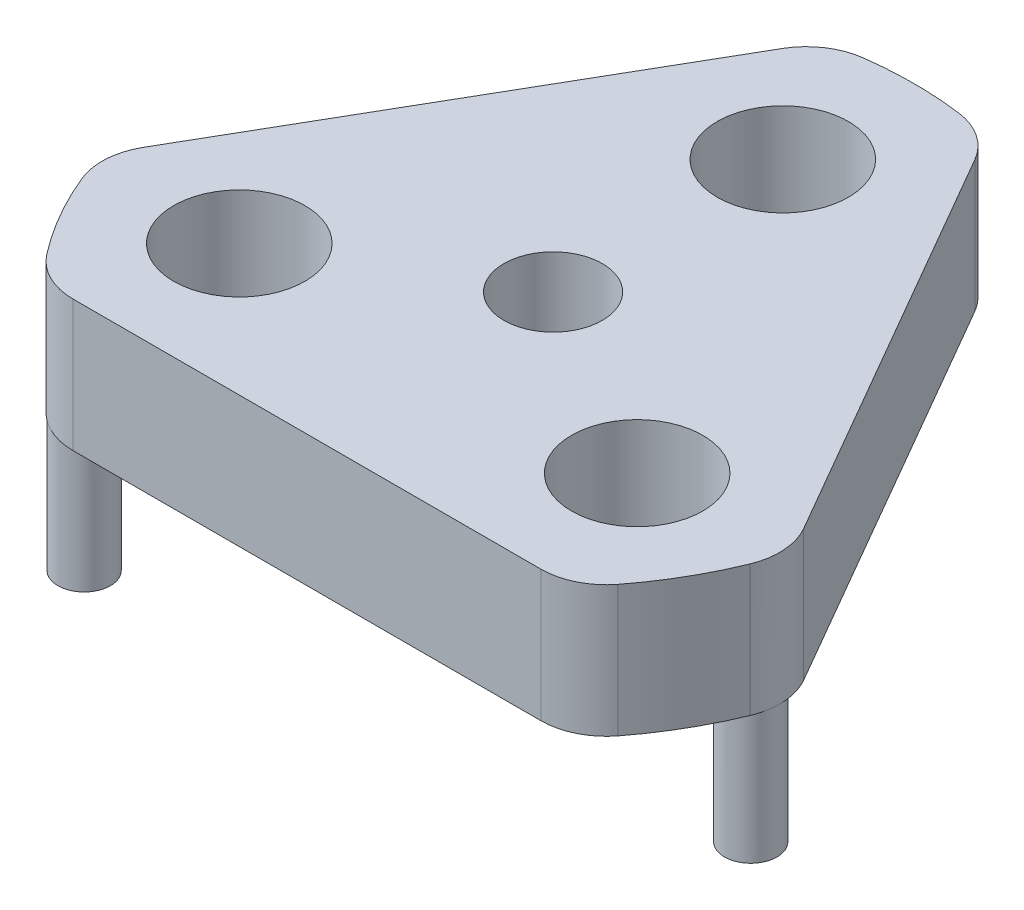
SolidWorks part; units mm, degrees
ref_plane "Alzado" through (0, 0, 0) normal (0, 0, 1) x (1, 0, 0)
ref_plane "Planta" through (0, 0, 0) normal (0, 1, 0) x (1, 0, 0)
ref_plane "Vista lateral" through (0, 0, 0) normal (1, 0, 0) x (0, 0, -1)
sketch "Croquis1" plane through (0, 0, 0) normal (0, 1, 0) x (1, 0, 0)
  line L0 (0, 7.5) -> (-6.4952, -3.75) construction
  line L1 (-6.4952, -3.75) -> (6.4952, -3.75) construction
  line L2 (6.4952, -3.75) -> (0, 7.5) construction
  line L3 (-6.4952, 3.75) -> (6.4952, 3.75) construction
  line L4 (6.4952, 3.75) -> (0, -7.5) construction
  line L5 (0, -7.5) -> (-6.4952, 3.75) construction
  line L6 (3.9952, 8.0801) -> (8.9952, -0.5801)
  line L7 (3.9952, 8.0801) -> (12.6554, 13.0801)
  line L8 (12.6554, 13.0801) -> (17.6554, 4.4199)
  line L9 (17.6554, 4.4199) -> (8.9952, -0.5801)
  line L10 (0, 17.5) -> (0, 7.5) construction
  line L11 (0, 22.5) -> (0, 27.5) construction
  line L12 (-6.1796, 26.7967) -> (-26.2964, -8.0467)
  line L13 (0, 17.5) -> (-15.1554, -8.75) construction
  line L14 (-15.1554, -8.75) -> (15.1554, -8.75) construction
  line L15 (15.1554, -8.75) -> (0, 17.5) construction
  line L16 (-20.1168, -18.75) -> (20.1168, -18.75)
  line L17 (6.1796, 26.7967) -> (26.2964, -8.0467)
  circle A0 centre (0, 0) radius 7.5 construction
  circle A1 centre (0, 0) radius 27.5
  arc A2 (-6.4952, -3.75) -> (6.4952, -3.75) centre (0, 3.75) ccw
  arc A3 (-6.4952, -3.75) -> (0, 7.5) centre (3.2476, -1.875) cw
  arc A4 (0, 7.5) -> (6.4952, -3.75) centre (-3.2476, -1.875) cw
  arc A5 (3.9952, 8.0801) -> (0, 7.5) centre (1.2701, 12.8001) cw
  arc A6 (8.9952, -0.5801) -> (6.4952, -3.75) centre (11.7203, -5.3001) ccw
  circle A7 centre (0, 17.5) radius 5
  arc A9 (3.9952, 8.0801) -> (-1.6662, 12.7858) centre (-5.2073, 2.7671) ccw
  arc A10 (12.6554, 13.0801) -> (1.6662, 22.2142) centre (-5.2073, 2.7671) ccw
  circle A11 centre (0, 17.5) radius 10 construction
  circle A12 centre (15.1554, -8.75) radius 5
  circle A13 centre (-15.1554, -8.75) radius 5
  circle A14 centre (0, 0) radius 3.75
  point P16 (6.4952, 3.75)
  point P37 (0, 0)
  dimension "D1" = 15
  dimension "D5" = 10
  dimension "D10" = 55
  dimension "D11" = 7.5
  dimension "D3" = 10
  dimension "D4" = 10
  dimension "D6" = 10
  dimension "D2" = 5
  dimension "D8" = 10
  dimension "D9" = 10
  dimension "D7" = 3
extrude "Saliente-Extruir3" add sketch "Croquis1" along normal blind 10 contours L16 A1 L17 L12 A13 A12 A10 L8 L9 A6 A2 A3 A5 A9 A7 | A4 A3 A2 A14 | A6 L6 A5 A4 | L9 L8 L7 L6 | L7 A10 A7 A9
fillet "Redondeo3" radius 5 6 edges at (-26.2964, 5, 8.0467) (-6.1796, 5, -26.7967) (6.1796, 5, -26.7967) (26.2964, 5, 8.0467) (20.1168, 5, 18.75) (-20.1168, 5, 18.75)
sketch "Croquis3" plane through (0, 0, 0) normal (0, -1, 0) x (1, 0, 0)
  line L0 (15.1554, 8.75) -> (23.806, 8.75) construction
  circle A0 centre (23.806, 8.75) radius 2
  arc A1 (25.1429, 6.0487) -> (25.4378, 10.4484) centre (20.8127, 8.5487) ccw construction
  circle A2 centre (-4.3253, -24.9916) radius 2
  circle A3 centre (-19.4807, 16.2416) radius 2
  point P5 (-10.0135, -26.9201)
  point P7 (0, 0)
  point P13 (0, 0)
  dimension "D1" = 4
  dimension "D2" = 3
extrude "Saliente-Extruir4" add sketch "Croquis3" along normal blind 10
equation "\"D8@Croquis1\"=\"D9@Croquis1\""
